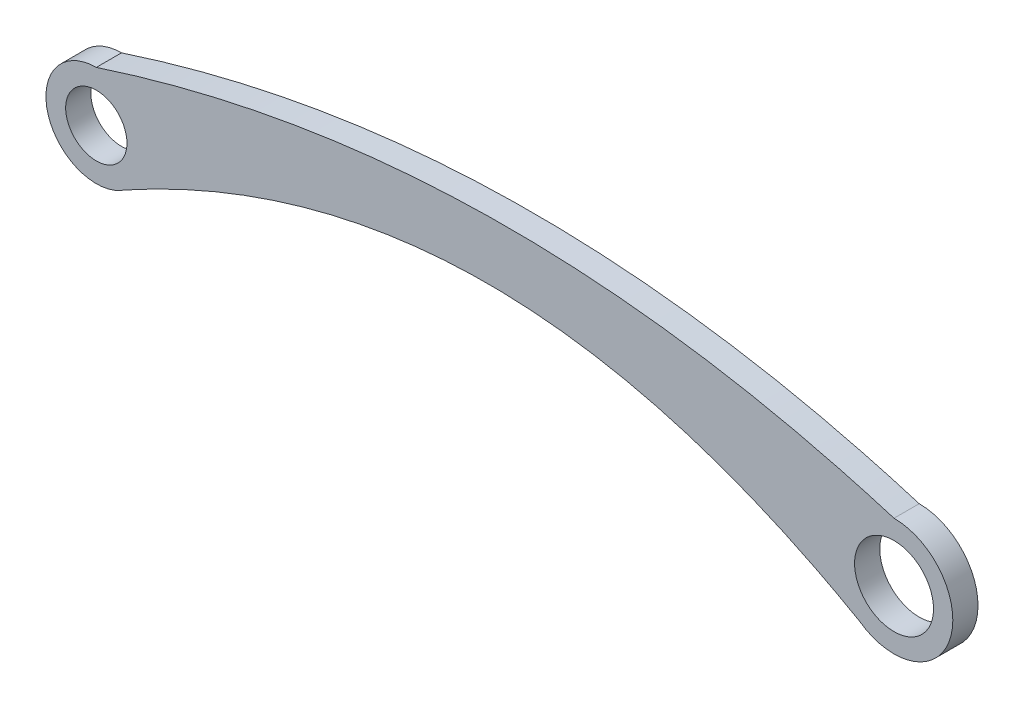
SolidWorks part; units mm, degrees
ref_plane "前视基准面" through (0, 0, 0) normal (0, 0, 1) x (1, 0, 0)
ref_plane "上视基准面" through (0, 0, 0) normal (0, 1, 0) x (1, 0, 0)
ref_plane "右视基准面" through (0, 0, 0) normal (1, 0, 0) x (0, 0, -1)
sketch "草图1" plane through (0, 0, 0) normal (0, 0, 1) x (1, 0, 0)
  line L0 (0, 7) -> (95, 7)
  line L1 (0, 0) -> (95, 0)
  line L2 (0, 0) -> (0, 14)
  line L3 (0, 14) -> (95, 14)
  line L4 (95, 0) -> (95, 14)
  line L5 (47.5, 21) -> (47.5, 14)
  circle A0 centre (95, 7) radius 7
  circle A1 centre (95, 7) radius 4.7
  circle A2 centre (0, 7) radius 3.65
  circle A3 centre (0, 7) radius 6
  circle A4 centre (47.5, 14) radius 7
  spline S0 degree 2 poles (0, 13) (47.346, 28.4984) (95, 14) knots 0 0 0 1 1 1
  spline S1 degree 2 poles (3.3859, 2.0467) (47.3998, 26.3275) (90.9268, 1.3071) knots 0 0 0 1 1 1
extrude "凸台-拉伸3" add sketch "草图1" along normal blind 3 contours L2 A3 A2 | L0 A3 L2 A2 | L2 A3 L0 A2 | A3 S1 L0 | L0 S1 A4 L3 S0 A3 | S0 L3 A4 | L3 S1 L5 S0 A4 | L3 A4 L5 | S0 A4 L3 | A4 S1 L0 A0 L3 | L0 S1 A0 | A1 L0 A0 L4 | A1 L4 A0 L0 | A1 L4 A0 | L3 S1 A4 | A4 S1 L3
